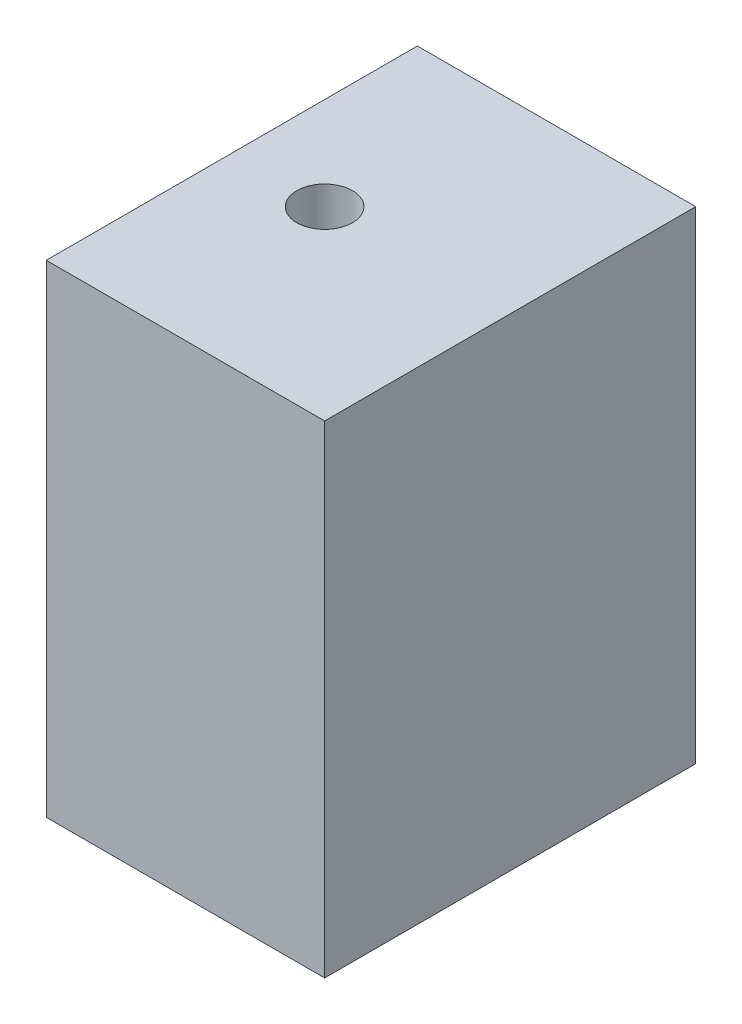
SolidWorks part; units mm, degrees
ref_plane "前视基准面" through (0, 0, 0) normal (0, 0, 1) x (1, 0, 0)
ref_plane "上视基准面" through (0, 0, 0) normal (0, 1, 0) x (1, 0, 0)
ref_plane "右视基准面" through (0, 0, 0) normal (1, 0, 0) x (0, 0, -1)
other "Configuration Table"
sketch "草图1" plane through (0, 0, 0) normal (0, 1, 0) x (1, 0, 0)
  line L1 (-7.5, 10) -> (7.5, 10)
  line L2 (-7.5, 10) -> (-7.5, -10)
  line L3 (-7.5, -10) -> (7.5, -10)
  line L4 (7.5, 10) -> (7.5, -10)
  line L5 (-7.5, 10) -> (7.5, -10) construction
  line L6 (-7.5, -10) -> (7.5, 10) construction
  point P0 (0, 0)
  dimension "D1" = 15
  dimension "D2" = 20
extrude "凸台-拉伸1" add sketch "草图1" along normal blind 26
sketch "草图3" plane through (0, 26, 0) normal (0, 1, 0) x (1, 0, 0)
  circle A1 centre (-2.5, 0) radius 1.5
  dimension "D1" = 3
extrude "切除-拉伸1" cut sketch "草图3" against normal through all both and the other way through all
